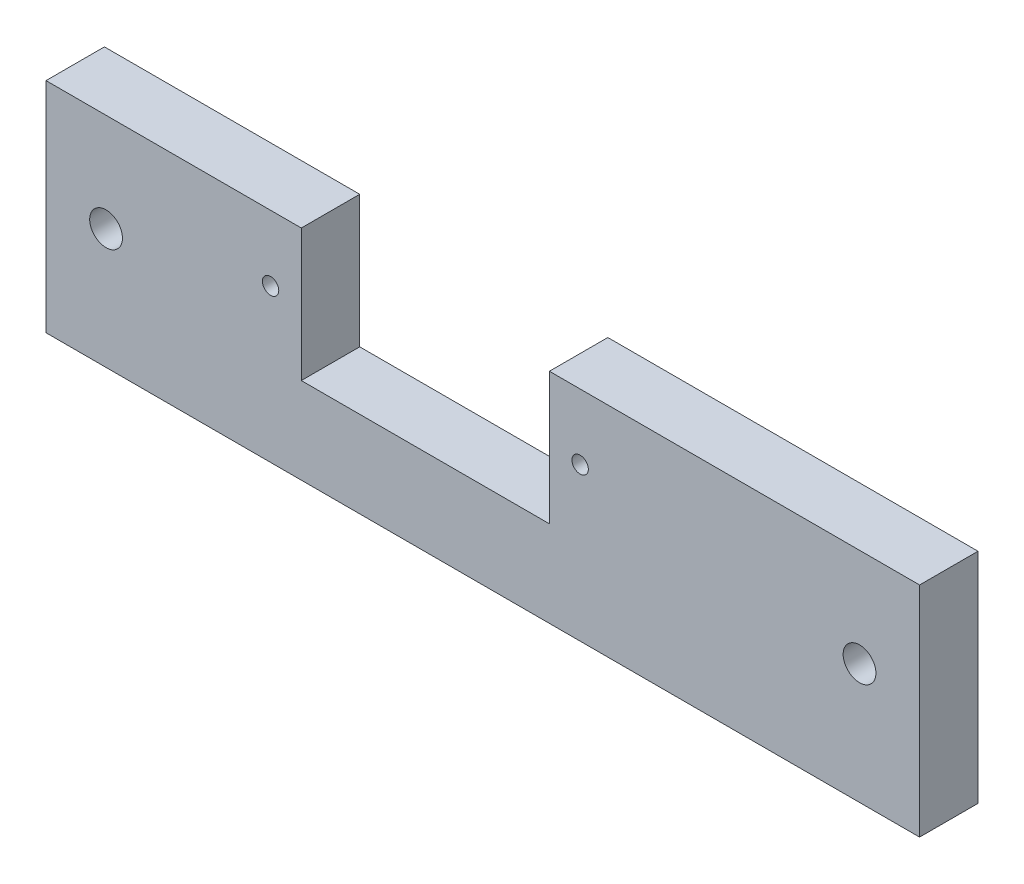
SolidWorks part; units mm, degrees
ref_plane "Front Plane" through (0, 0, 0) normal (0, 0, 1) x (1, 0, 0)
ref_plane "Top Plane" through (0, 0, 0) normal (0, 1, 0) x (1, 0, 0)
ref_plane "Right Plane" through (0, 0, 0) normal (1, 0, 0) x (0, 0, -1)
sketch "Model" plane through (0, 0, 0) normal (0, 0, 1) x (1, 0, 0)
  line L421 (46.1, 20) -> (46.1, 7.9)
  line L422 (23.38, 7.9) -> (23.38, 20)
  line L423 (46.1, 7.9) -> (23.38, 7.9)
  line L424 (80, 0) -> (0, 0)
  line L425 (80, 20) -> (80, 0)
  line L426 (46.1, 20) -> (80, 20)
  line L427 (0, 0) -> (0, 20)
  line L428 (0, 20) -> (23.38, 20)
  circle A75 centre (5.5, 11) radius 1.5
  circle A76 centre (74.5, 11) radius 1.5
  circle A77 centre (20.5663, 14) radius 0.75
  circle A78 centre (48.9137, 14) radius 0.75
  circle A79 centre (74.5, 11) radius 1.2
  circle A80 centre (5.5, 11) radius 1.2
extrude "Boss-Extrude1" add sketch "Model" along normal blind 5.35 contours L428 L427 L424 L425 L426 L421 L423 L422 A78 A77 A76 A75
